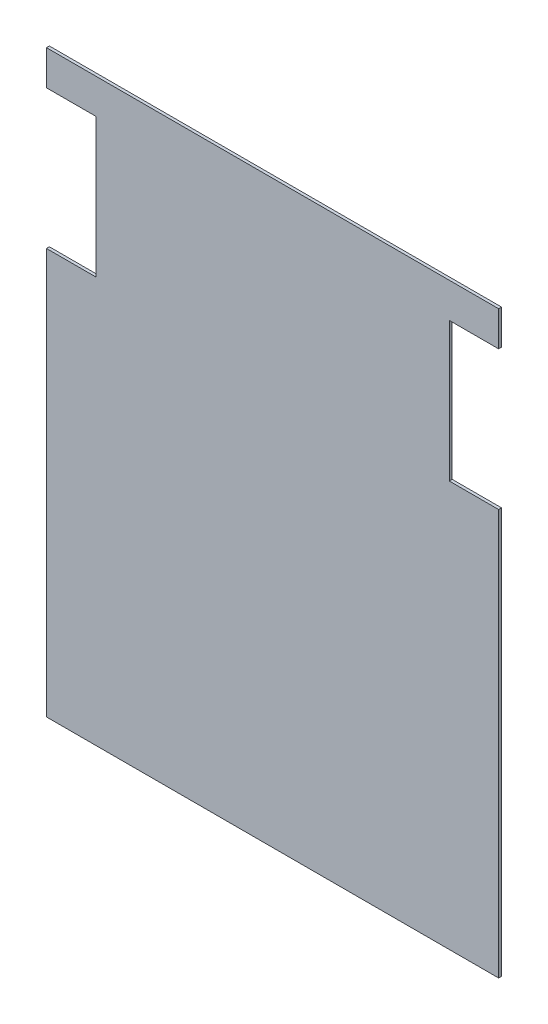
SolidWorks part; units mm, degrees
material "6061-T6 (SS)"
ref_plane "Front Plane" through (0, 0, 0) normal (0, 0, 1) x (1, 0, 0)
ref_plane "Top Plane" through (0, 0, 0) normal (0, 1, 0) x (1, 0, 0)
ref_plane "Right Plane" through (0, 0, 0) normal (1, 0, 0) x (0, 0, -1)
sketch "Sketch1" plane through (0, 0, 0) normal (0, 0, 1) x (1, 0, 0)
  line L0 (0, 0) -> (0, 19.5725) construction
  line L1 (-247.65, -317.5) -> (247.65, -317.5)
  line L2 (-247.65, -317.5) -> (-247.65, 317.5)
  line L3 (-247.65, 317.5) -> (247.65, 317.5)
  line L4 (247.65, -317.5) -> (247.65, 317.5)
  line L5 (-247.65, -317.5) -> (247.65, 317.5) construction
  line L6 (-247.65, 317.5) -> (247.65, -317.5) construction
  line L7 (247.65, 279.4) -> (193.675, 279.4)
  line L8 (247.65, 279.4) -> (247.65, 127)
  line L9 (247.65, 127) -> (193.675, 127)
  line L10 (193.675, 279.4) -> (193.675, 127)
  line L11 (-247.65, 127) -> (-193.675, 127)
  line L12 (-193.675, 279.4) -> (-193.675, 127)
  line L13 (-247.65, 279.4) -> (-193.675, 279.4)
  line L14 (-247.65, 279.4) -> (-247.65, 127)
  point P0 (0, 0)
  dimension "D1" = 495.3
  dimension "D2" = 635
  dimension "D3" = 38.1
  dimension "D4" = 190.5
  dimension "D5" = 53.975
extrude "Boss-Extrude1" add sketch "Sketch1" along normal blind 3.175 contours L2 L13 L12 L11 L1 L4 L9 L10 L7 L3
